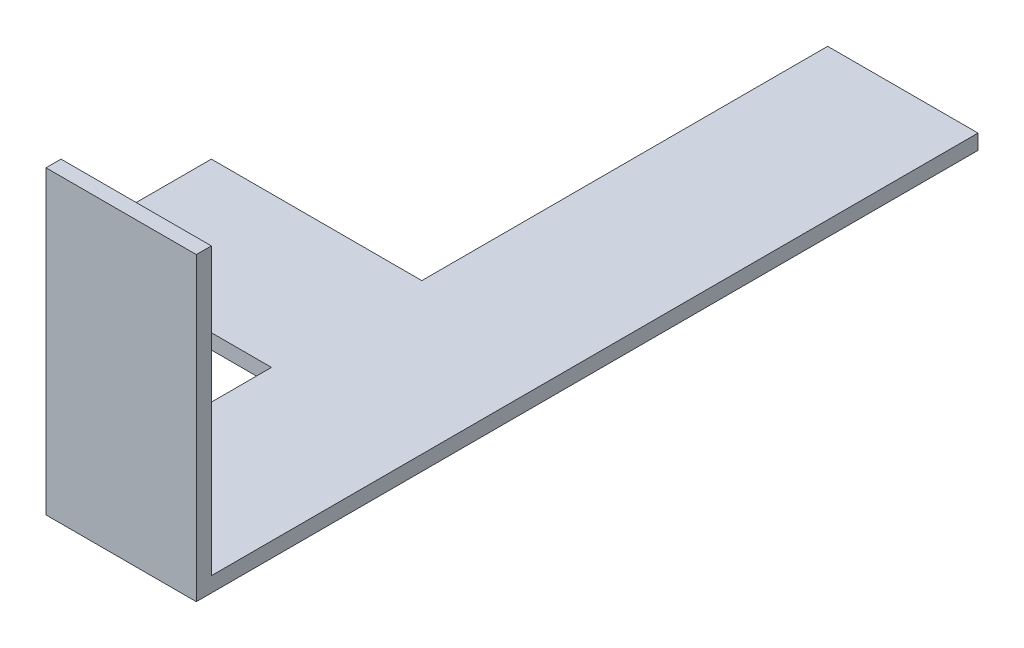
SolidWorks part; units mm, degrees
ref_plane "Front Plane" through (0, 0, 0) normal (0, 0, 1) x (1, 0, 0)
ref_plane "Top Plane" through (0, 0, 0) normal (0, 1, 0) x (1, 0, 0)
ref_plane "Right Plane" through (0, 0, 0) normal (1, 0, 0) x (0, 0, -1)
sketch "Sketch1" plane through (0, 0, 0) normal (0, 1, 0) x (1, 0, 0)
  line L0 (0, -27) -> (-14, -27)
  line L1 (0, 0) -> (10, 0)
  line L2 (0, 0) -> (0, -27)
  line L3 (0, -27) -> (10, -27)
  line L4 (10, 0) -> (10, -27)
  line L5 (0, -27) -> (10, -27)
  line L6 (0, -27) -> (0, -52)
  line L7 (0, -52) -> (10, -52)
  line L8 (10, -27) -> (10, -52)
  line L9 (-14, -27) -> (-14, -37)
  line L10 (-14, -37) -> (0, -37)
  dimension "D1" = 10
  dimension "D2" = 27
  dimension "D3" = 25
  dimension "D4" = 14
  dimension "D5" = 10
extrude "Boss-Extrude1" add sketch "Sketch1" along normal blind 1 contours L8 L3 L6 L7 | L4 L1 L2 L3 | L9 L10 L6 L0
sketch "Sketch2" plane through (0, 0, 0) normal (0, -1, 0) x (1, 0, 0)
  line L0 (10, 0) -> (10, 52) construction
  line L1 (0, 52) -> (10, 52)
  line L2 (0, 52) -> (0, 51)
  line L3 (0, 51) -> (10, 51)
  line L4 (10, 52) -> (10, 51)
  dimension "D1" = 1
extrude "Boss-Extrude2" add sketch "Sketch2" against normal blind 20
